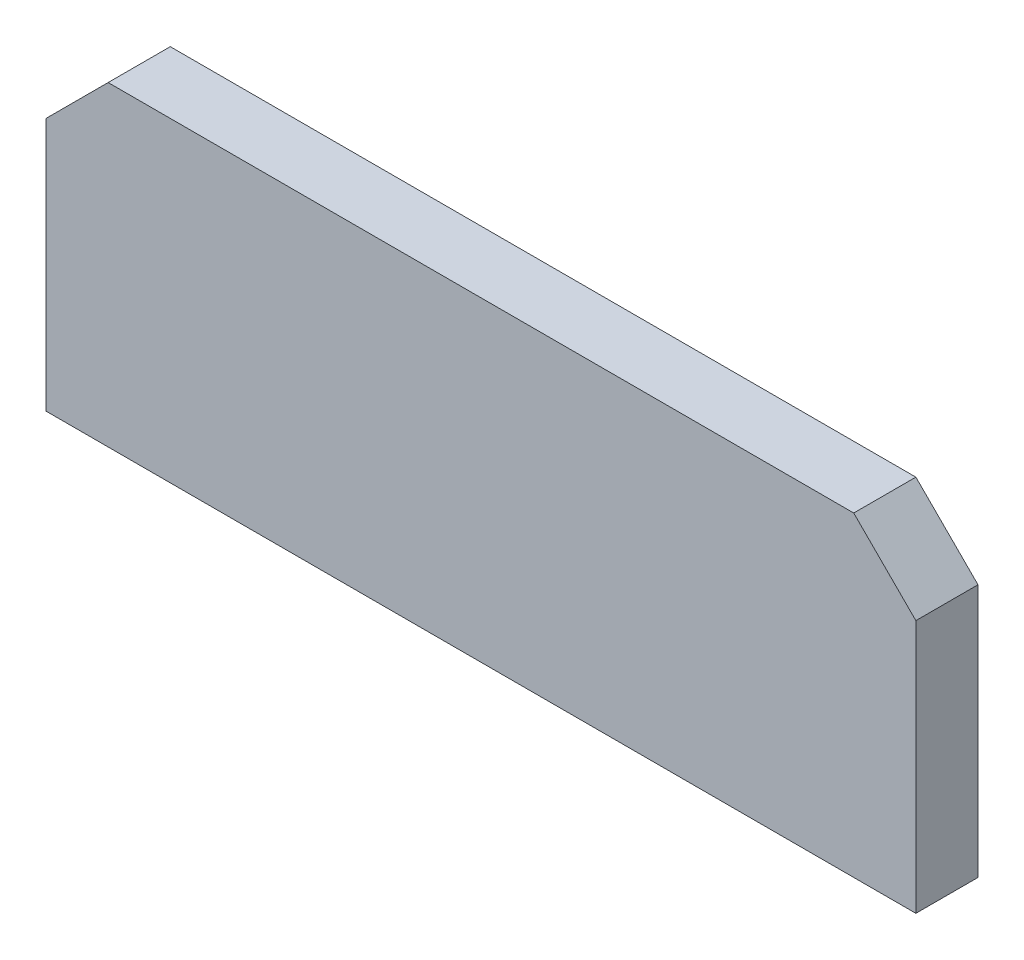
SolidWorks part; units mm, degrees
ref_plane "Alzado" through (0, 0, 0) normal (0, 0, 1) x (1, 0, 0)
ref_plane "Planta" through (0, 0, 0) normal (0, 1, 0) x (1, 0, 0)
ref_plane "Vista lateral" through (0, 0, 0) normal (1, 0, 0) x (0, 0, -1)
sketch "Croquis1" plane through (0, 0, 0) normal (0, 0, 1) x (1, 0, 0)
  line L0 (-60, 25.4) -> (-70, 15.4)
  line L1 (70, -25.4) -> (-70, -25.4)
  line L2 (70, -25.4) -> (70, 15.4)
  line L3 (60, 25.4) -> (-60, 25.4)
  line L4 (-70, -25.4) -> (-70, 15.4)
  line L5 (70, -25.4) -> (-70, 25.4) construction
  line L6 (70, 25.4) -> (-70, -25.4) construction
  line L7 (70, 15.4) -> (60, 25.4)
  point P0 (0, 0)
  dimension "D1" = 50.8
  dimension "D2" = 140
extrude "Saliente-Extruir1" add sketch "Croquis1" along normal blind 10
